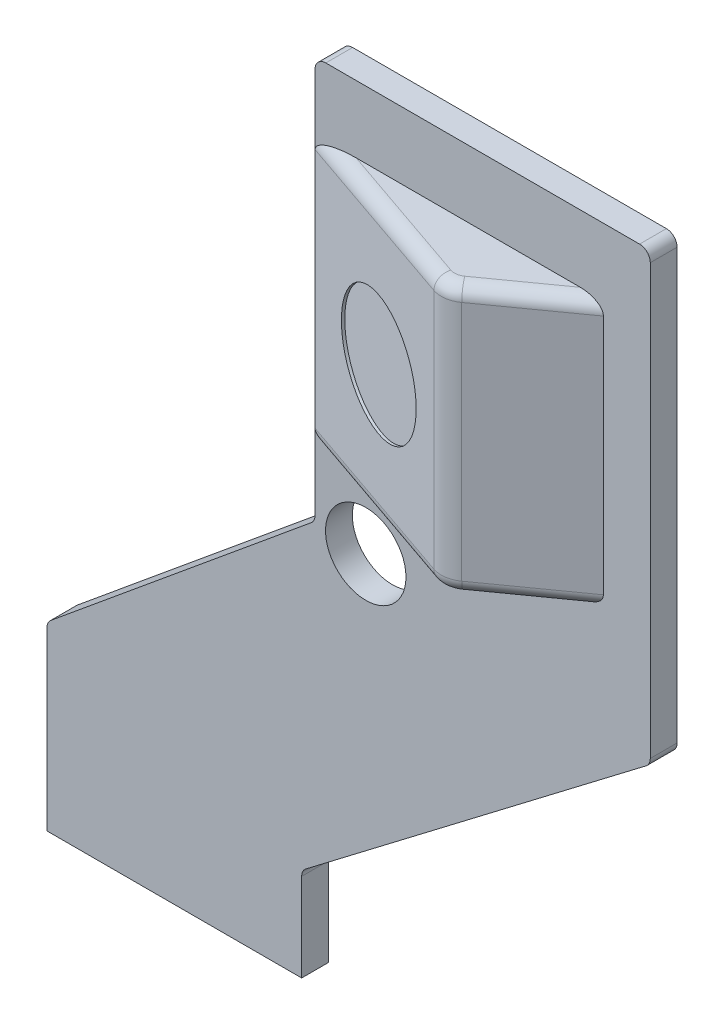
SolidWorks part; units mm, degrees
ref_plane "Front Plane" through (0, 0, 0) normal (0, 0, 1) x (1, 0, 0)
ref_plane "Top Plane" through (0, 0, 0) normal (0, 1, 0) x (1, 0, 0)
ref_plane "Right Plane" through (0, 0, 0) normal (1, 0, 0) x (0, 0, -1)
sketch "Sketch1" plane through (0, 0, 0) normal (0, 0, 1) x (1, 0, 0)
  line L0 (-22.5, 0) -> (26.508, 0) construction
  line L1 (-22.5, 30) -> (22.5, 30) construction
  line L2 (-22.5, 30) -> (-22.5, -30) construction
  line L3 (-22.5, -30) -> (22.5, -30) construction
  line L4 (22.5, 30) -> (22.5, -30) construction
  line L5 (-22.5, 30) -> (22.5, -30) construction
  line L6 (-22.5, -30) -> (22.5, 30) construction
  line L7 (-2.5, 30) -> (-2.5, -30) construction
  line L8 (-2.5, 30) -> (22.5, 30)
  line L9 (22.5, 30) -> (22.5, -3.2159)
  line L10 (22.5, -3.2159) -> (-3.5, -23.0389)
  line L11 (-3.5, -23.0389) -> (-3.5, -30)
  line L12 (-3.5, -30) -> (-22.5, -30)
  line L13 (-22.5, -30) -> (-22.5, -16.5)
  line L14 (-22.5, -16.5) -> (-2.5, 0)
  line L15 (-2.5, 0) -> (-2.5, 30)
  point P0 (0, 0)
  point P6 (-2.5, 30)
  point P7 (22.5, -3.2159)
  point P8 (-32.9435, 18.495)
  point P9 (-3.5, -30)
  point P10 (-22.5, -16.5)
  point P11 (-3.5, -23.0389)
  point P12 (-22.5, 0)
  dimension "D1" = 45
  dimension "D2" = 30
  dimension "D3" = 25
  dimension "D4" = 2.2
  dimension "D5" = 19
  dimension "D6" = 33.2159
extrude "Boss-Extrude1" add sketch "Sketch1" against normal blind 2
ref_plane "Plane1" through (0, 25, 0) normal (0, 1, 0) x (-1, 0, 0)
sketch "Sketch6" plane through (0, 25, 0) normal (0, 1, 0) x (-1, 0, 0)
  line L0 (-12, 5) -> (-12, 0) construction
  line L1 (2.5, 0) -> (-19, 0) construction
  line L2 (2.5, 0) -> (2.5, 5) construction
  line L3 (2.5, 5) -> (-19, 5) construction
  line L4 (-19, 0) -> (-19, 5) construction
  line L5 (2.5, 0) -> (-12, 5)
  line L6 (-12, 5) -> (-19, 0)
  line L7 (-19, 0) -> (2.5, 0)
extrude "Boss-Extrude3" add sketch "Sketch6" against normal blind 20
sketch "Sketch7" plane through (-0.2657, 0, 0.7705) normal (-0.326, 0, 0.9454) x (0.9454, 0, 0.326)
  line L0 (-2.3634, 15) -> (12.9744, 15) construction
  line L1 (-2.3634, 5) -> (-2.3634, 25) construction
  line L2 (12.9744, 5) -> (12.9744, 25) construction
  line L3 (5.3055, 25) -> (5.3055, 5) construction
  line L4 (-2.3634, 25) -> (12.9744, 25) construction
  line L5 (-2.3634, 5) -> (12.9744, 5) construction
  circle A0 centre (5.3055, 15) radius 4.5
  dimension "D1" = 9
extrude "Cut-Extrude1" cut sketch "Sketch7" against normal blind 0.2
sketch "Sketch8" plane through (0, 0, 0) normal (0, 0, 1) x (1, 0, 0)
  line L0 (22.5, -3.2159) -> (-21.0428, -3.2159) construction
  line L1 (1.2792, -3.2159) -> (1.2792, 2.7841) construction
  circle A0 centre (1.2792, -0.2159) radius 3
  point P4 (1.2792, -0.2159)
  dimension "D1" = 6
extrude "Cut-Extrude2" cut sketch "Sketch8" against normal through all
fillet "Fillet3" radius 2 1 edges at (12, 15, 5)
fillet "Fillet4" radius 1 6 edges at (11.9641, 5, 4.7523) (15.9197, 5, 2.2002) (11.9641, 25, 4.7523) (15.9197, 25, 2.2002)
fillet "Fillet5" radius 0.8 6 edges at (-2.5, 0, -1) (-22.5, -16.5, -1) (-3.5, -23.0389, -1) (22.5, -3.2159, -1) (-2.5, 30, -1) (22.5, 30, -1)
